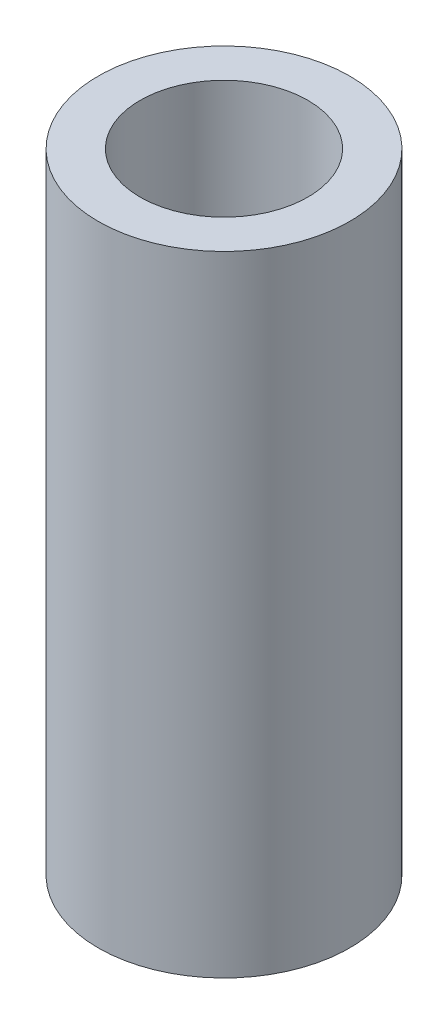
SolidWorks part; units mm, degrees
ref_plane "Front Plane" through (0, 0, 0) normal (0, 0, 1) x (1, 0, 0)
ref_plane "Top Plane" through (0, 0, 0) normal (0, 1, 0) x (1, 0, 0)
ref_plane "Right Plane" through (0, 0, 0) normal (1, 0, 0) x (0, 0, -1)
sketch "Sketch1" plane through (0, 0, 0) normal (0, 1, 0) x (1, 0, 0)
  circle A0 centre (0, 0) radius 3
  dimension "D1" = 6
extrude "Boss-Extrude1" add sketch "Sketch1" along normal blind 15
sketch "Sketch2" plane through (0, 15, 0) normal (0, 1, 0) x (1, 0, 0)
  circle A0 centre (0, 0) radius 2
  dimension "D1" = 4
extrude "Cut-Extrude1" cut sketch "Sketch2" against normal through all
